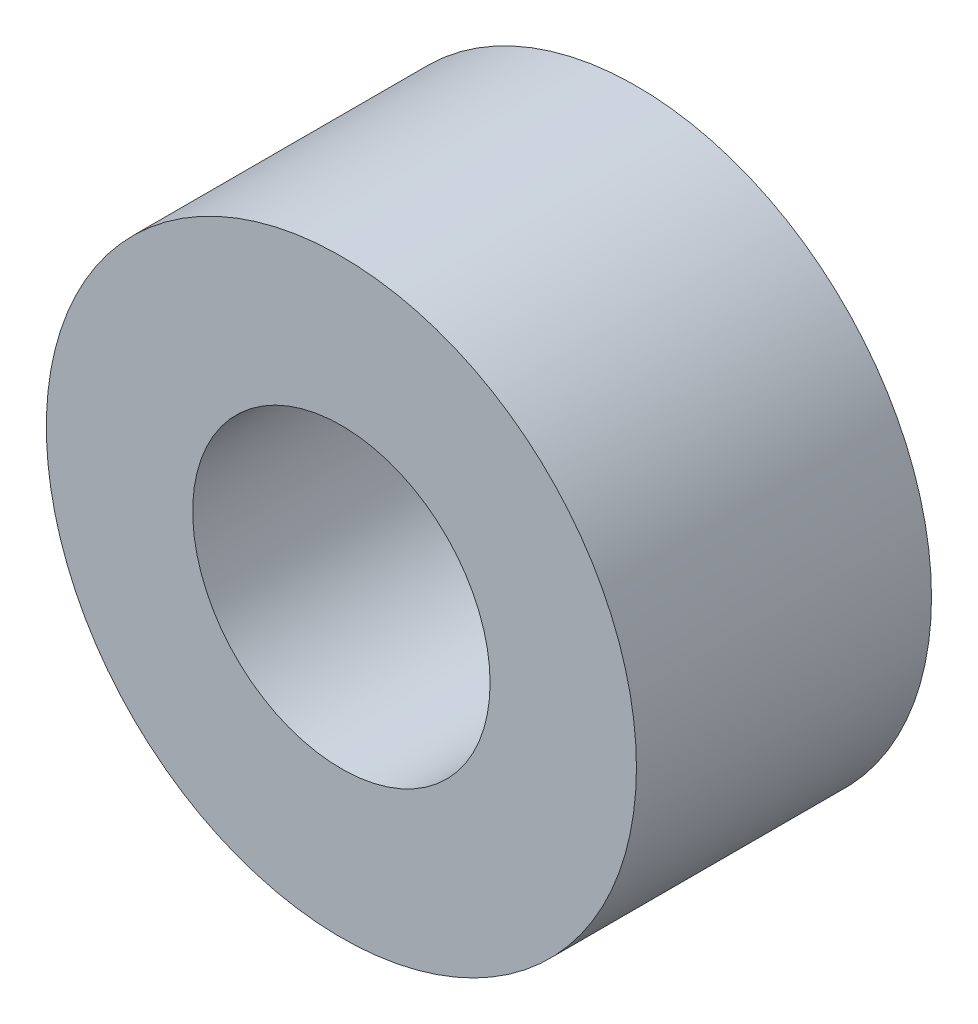
SolidWorks part; units mm, degrees
ref_plane "Front Plane" through (0, 0, 0) normal (0, 0, 1) x (1, 0, 0)
ref_plane "Top Plane" through (0, 0, 0) normal (0, 1, 0) x (1, 0, 0)
ref_plane "Right Plane" through (0, 0, 0) normal (1, 0, 0) x (0, 0, -1)
sketch "Sketch1" plane through (0, 0, 0) normal (0, 0, 1) x (1, 0, 0)
  circle A0 centre (0, 0) radius 6.35
  circle A1 centre (0, 0) radius 3.2004
  dimension "OD" = 12.7
  dimension "ID" = 6.4008
extrude "Extrude1" add sketch "Sketch1" along normal mid plane 6.35
sketch "Sketch2" plane through (0, 0, 0) normal (1, 0, 0) x (0, 0, -1)
  line L0 (-3.175, -3.2004) -> (3.175, -3.2004) construction
  line L3 (3.175, 3.2004) -> (-3.175, 3.2004) construction
  line L5 (-3.175, -3.2004) -> (3.175, -3.2004)
  line L6 (3.175, 3.2004) -> (-3.175, 3.2004)
sketch "Sketch4" plane through (0, 0, 3.175) normal (0, 0, 1) x (1, 0, 0)
  line L0 (0, 0) -> (-2.263, 2.263)
  line L1 (0, -3.4925) -> (0, 3.4925) construction
  circle A0 centre (0, 0) radius 3.2004 construction
  dimension "D1" = 45
